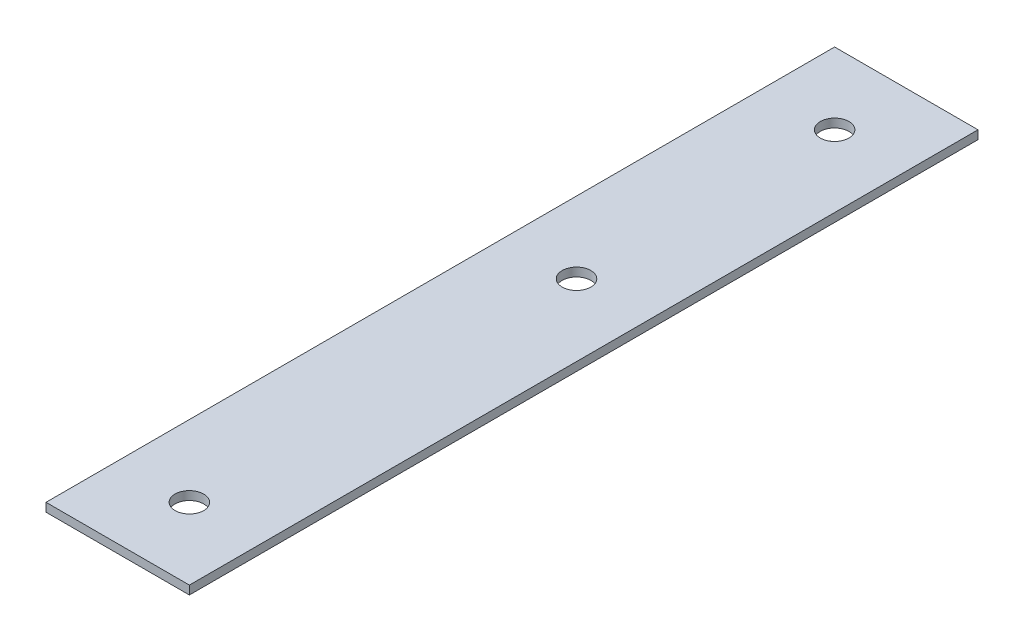
SolidWorks part; units mm, degrees
ref_plane "Front Plane" through (0, 0, 0) normal (0, 0, 1) x (1, 0, 0)
ref_plane "Top Plane" through (0, 0, 0) normal (0, 1, 0) x (1, 0, 0)
ref_plane "Right Plane" through (0, 0, 0) normal (1, 0, 0) x (0, 0, -1)
sketch "Sketch1" plane through (0, 0, 0) normal (0, 1, 0) x (1, 0, 0)
  line L1 (0, 0) -> (50, 0)
  line L2 (0, 0) -> (0, 275)
  line L3 (0, 275) -> (50, 275)
  line L4 (50, 0) -> (50, 275)
  dimension "D1" = 50
  dimension "D2" = 275
extrude "Boss-Extrude1" add sketch "Sketch1" along normal blind 3
sketch "Sketch2" plane through (0, 3, 0) normal (0, 1, 0) x (1, 0, 0)
  line L0 (0, 275) -> (0, 0) construction
  line L1 (50, 275) -> (0, 275) construction
  line L2 (0, 0) -> (50, 0) construction
  circle A0 centre (25, 250) radius 5
  circle A1 centre (25, 25) radius 5
  circle A2 centre (25, 160) radius 5
  point P8 (25, 275)
  dimension "D3" = 10
  dimension "D4" = 10
  dimension "D7" = 10
  dimension "D1" = 25
  dimension "D2" = 25
  dimension "D5" = 25
  dimension "D6" = 25
  dimension "D8" = 25
  dimension "D9" = 135
extrude "Cut-Extrude1" cut sketch "Sketch2" against normal through all
